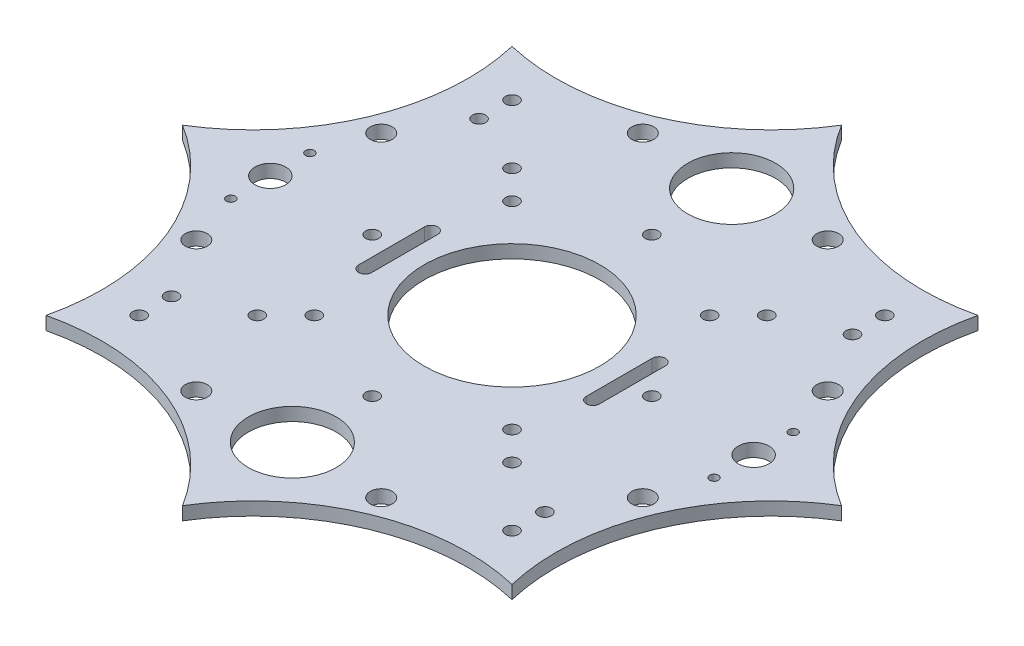
SolidWorks part; units mm, degrees
ref_plane "前基準面" through (0, 0, 0) normal (0, 0, 1) x (1, 0, 0)
ref_plane "上基準面" through (0, 0, 0) normal (0, 1, 0) x (1, 0, 0)
ref_plane "右基準面" through (0, 0, 0) normal (1, 0, 0) x (0, 0, -1)
sketch "草圖1" plane through (0, 0, 0) normal (0, 1, 0) x (1, 0, 0)
  line L0 (-53.033, 53.033) -> (53.033, -53.033) construction
  line L1 (53.033, 53.033) -> (-53.033, -53.033) construction
  line L2 (0, 0) -> (0, 75) construction
  line L3 (-28.9914, 28.9914) -> (28.9914, -28.9914) construction
  line L4 (0, 0) -> (28.9914, -28.9914) construction
  line L5 (0, 0) -> (-28.9914, -28.9914) construction
  line L6 (-75, 0) -> (75, 0) construction
  line L7 (0, -75) -> (0, 75) construction
  line L8 (-22.5, 22.5) -> (22.5, 22.5) construction
  line L9 (22.5, 22.5) -> (22.5, -22.5) construction
  line L10 (22.5, -22.5) -> (-22.5, -22.5) construction
  line L11 (-22.5, -22.5) -> (-22.5, 22.5) construction
  line L12 (0, 31.8198) -> (31.8198, 0) construction
  line L13 (31.8198, 0) -> (0, -31.8198) construction
  line L14 (0, -31.8198) -> (-31.8198, 0) construction
  line L15 (-31.8198, 0) -> (0, 31.8198) construction
  line L16 (-22.961, 55.4328) -> (0, 0) construction
  line L17 (-31.8198, 0) -> (-20, 0) construction
  line L18 (-31.8198, 0) -> (-20, 0) construction
  line L19 (-20, 0) -> (-25.9099, 0) construction
  line L20 (-25.9099, 0) -> (-25.9099, -8.1379) construction
  line L21 (20, 0) -> (31.8198, 0) construction
  line L22 (31.8198, 0) -> (25.9099, 0) construction
  line L23 (25.9099, 0) -> (25.9099, -8.1379) construction
  line L24 (-25.9099, 7.5) -> (-25.9099, -7.5) construction
  line L25 (-24.4099, 7.5) -> (-24.4099, -7.5)
  line L26 (-27.4099, 7.5) -> (-27.4099, -7.5)
  line L27 (25.9099, 7.5) -> (25.9099, -7.5) construction
  line L28 (27.4099, 7.5) -> (27.4099, -7.5)
  line L29 (24.4099, 7.5) -> (24.4099, -7.5)
  circle A0 centre (0, 0) radius 75 construction
  circle A1 centre (-42.4264, 42.4264) radius 1.5
  circle A2 centre (-28.9914, 28.9914) radius 1.5
  circle A3 centre (28.9914, -28.9914) radius 1.5
  circle A4 centre (42.4264, -42.4264) radius 1.5
  circle A5 centre (42.4264, 42.4264) radius 1.5
  circle A6 centre (28.9914, 28.9914) radius 1.5
  circle A7 centre (-28.9914, -28.9914) radius 1.5
  circle A8 centre (-42.4264, -42.4264) radius 1.5
  circle A9 centre (42.4264, -42.4264) radius 1.5
  circle A10 centre (28.9914, -28.9914) radius 1.5
  circle A11 centre (-28.9914, 28.9914) radius 1.5
  circle A12 centre (-42.4264, 42.4264) radius 1.5
  circle A13 centre (-42.4264, -42.4264) radius 1.5
  circle A14 centre (-28.9914, -28.9914) radius 1.5
  circle A15 centre (28.9914, 28.9914) radius 1.5
  circle A16 centre (42.4264, 42.4264) radius 1.5
  circle A17 centre (0, 0) radius 20
  circle A18 centre (0, 31.8198) radius 1.5
  circle A19 centre (31.8198, 0) radius 1.5
  circle A20 centre (22.5, 22.5) radius 1.5
  circle A21 centre (0, -31.8198) radius 1.5
  circle A22 centre (-22.5, -22.5) radius 1.5
  circle A23 centre (-31.8198, 0) radius 1.5
  circle A24 centre (-22.5, 22.5) radius 1.5
  circle A25 centre (22.5, -22.5) radius 1.5
  arc A26 (-53.033, 53.033) -> (0, 75) centre (-41.7036, 100.6815) ccw
  arc A27 (0, 75) -> (53.033, 53.033) centre (41.7036, 100.6815) ccw
  arc A28 (53.033, 53.033) -> (75, 0) centre (100.6815, 41.7036) ccw
  arc A29 (75, 0) -> (53.033, -53.033) centre (100.6815, -41.7036) ccw
  arc A30 (53.033, -53.033) -> (0, -75) centre (41.7036, -100.6815) ccw
  arc A31 (0, -75) -> (-53.033, -53.033) centre (-41.7036, -100.6815) ccw
  arc A32 (-53.033, -53.033) -> (-75, 0) centre (-100.6815, -41.7036) ccw
  arc A33 (-75, 0) -> (-53.033, 53.033) centre (-100.6815, 41.7036) ccw
  circle A34 centre (-21.0476, 50.8134) radius 2.5
  arc A35 (-24.4099, 7.5) -> (-27.4099, 7.5) centre (-25.9099, 7.5) ccw
  arc A36 (-27.4099, -7.5) -> (-24.4099, -7.5) centre (-25.9099, -7.5) ccw
  arc A37 (27.4099, 7.5) -> (24.4099, 7.5) centre (25.9099, 7.5) ccw
  arc A38 (24.4099, -7.5) -> (27.4099, -7.5) centre (25.9099, -7.5) ccw
  circle A39 centre (21.0476, 50.8134) radius 2.5
  circle A40 centre (50.8134, 21.0476) radius 2.5
  circle A41 centre (50.8134, -21.0476) radius 2.5
  circle A42 centre (21.0476, -50.8134) radius 2.5
  circle A43 centre (-21.0476, -50.8134) radius 2.5
  circle A44 centre (-50.8134, -21.0476) radius 2.5
  circle A45 centre (-50.8134, 21.0476) radius 2.5
  circle A46 centre (0, 50) radius 10
  circle A48 centre (0, -50) radius 10
  circle A50 centre (-50, 0) radius 10 [skipped]
  circle A51 centre (50, 0) radius 10 [skipped]
  point P89 (-25.9099, 0)
  point P94 (25.9099, 0)
  dimension "D2" = 3
  dimension "D3" = 3
  dimension "D4" = 3
  dimension "D5" = 3
  dimension "D9" = 150
  dimension "D12" = 40
  dimension "D14" = 3
  dimension "D16" = 5
  dimension "D18" = 8
  dimension "D24" = 20
  dimension "D1" = 45
  dimension "D6" = 19
  dimension "D7" = 19
  dimension "D8" = 120
  dimension "D11" = 90
  dimension "D13" = 45
  dimension "D15" = 45
  dimension "D17" = 5
  dimension "D19" = 60
  dimension "D20" = 3
  dimension "D21" = 3
  dimension "D22" = 15
  dimension "D23" = 50
  dimension "D10" = 4
  dimension "D25" = 4
extrude "填料-伸長2" add sketch "草圖1" along normal blind 3
sketch "草圖2" plane through (0, 3, 0) normal (0, 1, 0) x (1, 0, 0)
  line L1 (-55, 9) -> (55, 9) construction
  line L2 (-55, 9) -> (-55, -9) construction
  line L3 (-55, -9) -> (55, -9) construction
  line L4 (55, 9) -> (55, -9) construction
  line L5 (-55, 9) -> (55, -9) construction
  line L6 (-55, -9) -> (55, 9) construction
  circle A0 centre (-55, 9) radius 1
  circle A1 centre (-55, -9) radius 1
  circle A2 centre (55, 9) radius 1
  circle A3 centre (55, -9) radius 1
  circle A4 centre (-55, 0) radius 3.5
  circle A5 centre (55, 0) radius 3.5
  point P0 (0, 0)
  dimension "D3" = 2
  dimension "D4" = 7
  dimension "D5" = 7
  dimension "D1" = 18
  dimension "D2" = 110
extrude "除料-伸長1" cut sketch "草圖2" against normal blind 3
sketch "草圖3" plane through (0, 3, 0) normal (0, 1, 0) x (1, 0, 0)
  line L1 (-42.5, 35) -> (42.5, 35) construction
  line L2 (-42.5, 35) -> (-42.5, -35) construction
  line L3 (-42.5, -35) -> (42.5, -35) construction
  line L4 (42.5, 35) -> (42.5, -35) construction
  line L5 (-42.5, 35) -> (42.5, -35) construction
  line L6 (-42.5, -35) -> (42.5, 35) construction
  circle A0 centre (-42.5, 35) radius 1.5
  circle A1 centre (42.5, 35) radius 1.5
  circle A2 centre (42.5, -35) radius 1.5
  circle A3 centre (-42.5, -35) radius 1.5
  point P0 (0, 0)
  dimension "D3" = 3
  dimension "D1" = 85
  dimension "D2" = 70
extrude "除料-伸長2" cut sketch "草圖3" against normal blind 10
